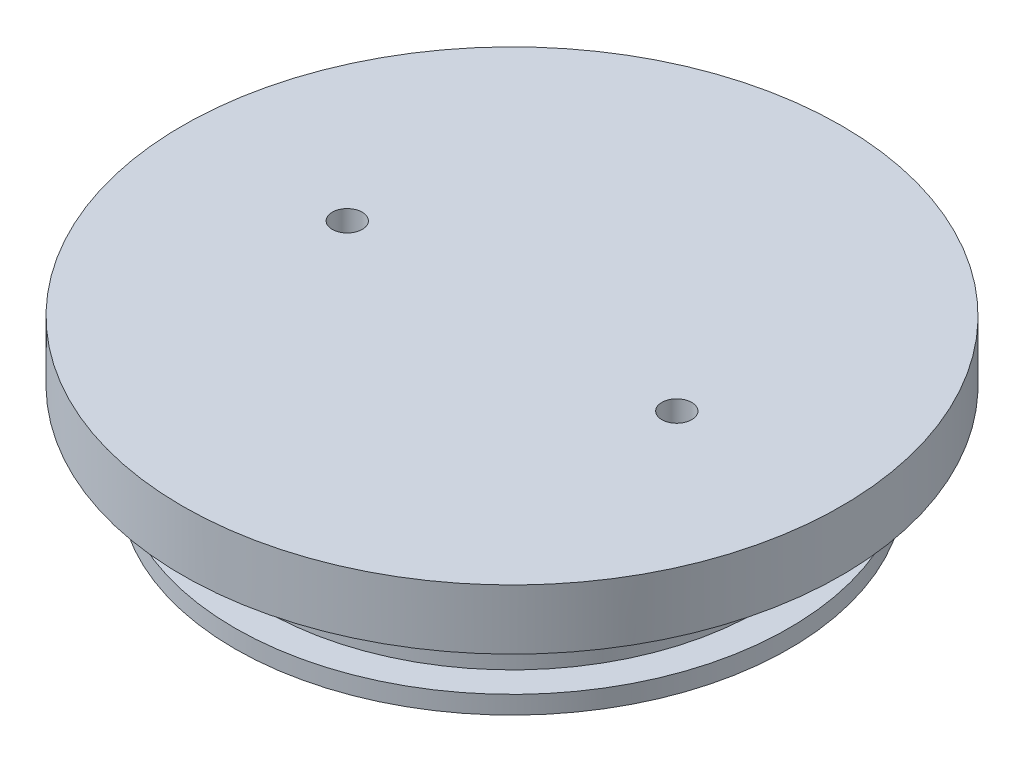
SolidWorks part; units mm, degrees
ref_plane "前视基准面" through (0, 0, 0) normal (0, 0, 1) x (1, 0, 0)
ref_plane "上视基准面" through (0, 0, 0) normal (0, 1, 0) x (1, 0, 0)
ref_plane "右视基准面" through (0, 0, 0) normal (1, 0, 0) x (0, 0, -1)
sketch "草图1" plane through (0, 0, 0) normal (0, 1, 0) x (1, 0, 0)
  circle A0 centre (0, 0) radius 11
  dimension "D1" = 22
extrude "凸台-拉伸1" add sketch "草图1" along normal blind 9
sketch "草图2" plane through (0, 9, 0) normal (0, 1, 0) x (1, 0, 0)
  circle A0 centre (-5.5, 0) radius 0.5
  circle A1 centre (5.5, 0) radius 0.5
  dimension "D1" = 1
  dimension "D2" = 1
  dimension "D3" = 11
  dimension "D4" = 5.5
extrude "切除-拉伸1" cut sketch "草图2" against normal through all
sketch "草图3" plane through (0, 0, 0) normal (0, -1, 0) x (1, 0, 0)
  circle A0 centre (0, 0) radius 9.25
  circle A1 centre (0, 0) radius 16.5491
  dimension "D1" = 18.5
extrude "切除-拉伸2" cut sketch "草图3" against normal blind 7
sketch "草图4" plane through (0, 0, 0) normal (0, 0, 1) x (1, 0, 0)
  line L0 (-9.25, 7) -> (-9.25, 0) construction
  line L1 (-10.25, 6.3) -> (-8.25, 6.3)
  line L2 (-10.25, 6.3) -> (-10.25, 4.6)
  line L3 (-10.25, 4.6) -> (-8.25, 4.6)
  line L4 (-8.25, 6.3) -> (-8.25, 4.6)
  line L5 (-10.25, 6.3) -> (-8.25, 4.6) construction
  line L6 (-10.25, 4.6) -> (-8.25, 6.3) construction
  line L7 (-9.25, 0) -> (9.25, 0) construction
  line L8 (-10.25, 3.2) -> (-8.25, 3.2)
  line L9 (-10.25, 3.2) -> (-10.25, 1.5)
  line L10 (-10.25, 1.5) -> (-8.25, 1.5)
  line L11 (-8.25, 3.2) -> (-8.25, 1.5)
  line L12 (-10.25, 3.2) -> (-8.25, 1.5) construction
  line L13 (-10.25, 1.5) -> (-8.25, 3.2) construction
  line L14 (0, 0) -> (0, 12.2991) construction
  point P0 (-9.25, 5.45)
  point P7 (-9.25, 2.35)
  dimension "D1" = 1.7
  dimension "D2" = 1.7
  dimension "D3" = 1.5
  dimension "D4" = 1.4
  dimension "D5" = 2
  dimension "D6" = 2
revolve "切除-旋转1" cut sketch "草图4" angle 360 about L14
sketch "草图5" plane through (0, 0, 0) normal (0, -1, 0) x (1, 0, 0)
  line L1 (-2.5, 3) -> (2.5, 3)
  line L2 (-2.5, 3) -> (-2.5, -3)
  line L3 (-2.5, -3) -> (2.5, -3)
  line L4 (2.5, 3) -> (2.5, -3)
  line L5 (-2.5, 3) -> (2.5, -3) construction
  line L6 (-2.5, -3) -> (2.5, 3) construction
  point P0 (0, 0)
  dimension "D1" = 6
  dimension "D2" = 5
extrude "切除-拉伸3" cut sketch "草图5" against normal blind 7
sketch "草图6" plane through (0, 9, 0) normal (0, 1, 0) x (1, 0, 0)
  circle A0 centre (0, 0) radius 1.4
  dimension "D1" = 2.8
extrude "切除-拉伸4" [suppressed] cut sketch "草图6" against normal blind 7
sketch "草图7" plane through (0, 9, 0) normal (0, 1, 0) x (1, 0, 0)
  circle A0 centre (-5.5, 0) radius 1.25
  circle A1 centre (5.5, 0) radius 1.25
  dimension "D1" = 2.5
  dimension "D2" = 2.5
extrude "切除-拉伸5" [suppressed] cut sketch "草图7" against normal blind 2.5
sketch "草图8" plane through (0, 0, 0) normal (0, -1, 0) x (1, 0, 0)
  circle A0 centre (-5.5, 0) radius 1.25
  circle A1 centre (5.5, 0) radius 1.25
  dimension "D1" = 2.5
  dimension "D2" = 2.5
extrude "切除-拉伸6" cut sketch "草图8" against normal blind 1.5
sketch "草图9" plane through (0, 0, 0) normal (0, -1, 0) x (1, 0, 0)
  line L0 (-2.5, 3) -> (-2.5, -3) construction
  line L1 (2.5, 3) -> (-2.5, 3) construction
  line L2 (2.5, -3) -> (2.5, 3) construction
  line L4 (-2.5, -3) -> (2.5, -3) construction
  line L5 (-2.5, -3) -> (2.5, -3)
  line L6 (2.5, -3) -> (2.5, 3)
  line L7 (2.5, 3) -> (-2.5, 3)
  line L8 (-2.5, 3) -> (-2.5, -3)
  line L9 (3.5, 4) -> (-3.5, 4)
  line L10 (-3.5, 4) -> (-3.5, -4)
  line L11 (-3.5, -4) -> (3.5, -4)
  line L12 (3.5, -4) -> (3.5, 4)
  circle A1 centre (0, 0) radius 9.25
  circle A10 centre (0, 0) radius 9.25
  line M5 (-2.5, 3) -> (2.5, 3)
  line M6 (2.5, 3) -> (2.5, -3)
  line M7 (2.5, -3) -> (-2.5, -3)
  line M8 (-2.5, -3) -> (-2.5, 3)
  dimension "D1" = 0
  dimension "D2" = 1
extrude "切除-拉伸7" cut sketch "草图9" against normal blind 2 contours L11 L12 L9 L10 M8 M5 M6 M7
chamfer "倒角1" distance 0.5 angle 45 1 edges at (0, 0, -9.25)
sketch "草图10" plane through (0, 0, 0) normal (0, -1, 0) x (-1, 0, 0)
  circle A0 centre (0, 0) radius 16.7056
extrude "切除-拉伸8" cut sketch "草图10" against normal blind 4
sketch "草图11" plane through (0, 4, 0) normal (0, -1, 0) x (1, 0, 0)
  circle A0 centre (-5.5, 0) radius 2
  circle A1 centre (5.5, 0) radius 2
  dimension "D1" = 4
  dimension "D2" = 4
extrude "切除-拉伸9" cut sketch "草图11" against normal blind 3
sketch "草图12" plane through (0, 4, 0) normal (0, -1, 0) x (1, 0, 0)
  line L1 (-2.75, 4.765) -> (2.75, 4.765)
  line L2 (-2.75, 4.765) -> (-2.75, -4.765)
  line L3 (-2.75, -4.765) -> (2.75, -4.765)
  line L4 (2.75, 4.765) -> (2.75, -4.765)
  line L5 (-2.75, 4.765) -> (2.75, -4.765) construction
  line L6 (-2.75, -4.765) -> (2.75, 4.765) construction
  circle A0 centre (-2.75, 4.765) radius 1.25
  circle A1 centre (2.75, 4.765) radius 1.25
  circle A2 centre (2.75, -4.765) radius 1.25
  circle A3 centre (-2.75, -4.765) radius 1.25
  point P0 (0, 0)
  dimension "D3" = 2.5
  dimension "D4" = 2.5
  dimension "D5" = 2.5
  dimension "D6" = 2.5
  dimension "D1" = 5.5
  dimension "D2" = 9.53
extrude "切除-拉伸10" cut sketch "草图12" against normal blind 3 contours A3 | A2 | A1 | A0
